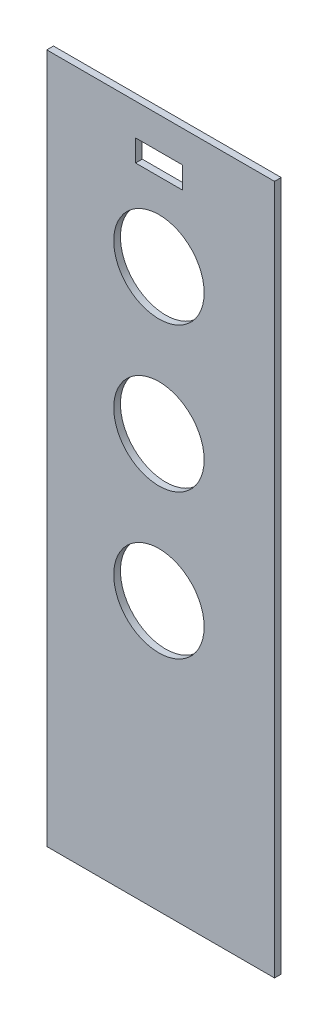
SolidWorks part; units mm, degrees
ref_plane "Front Plane" through (0, 0, 0) normal (0, 0, 1) x (1, 0, 0)
ref_plane "Top Plane" through (0, 0, 0) normal (0, 1, 0) x (1, 0, 0)
ref_plane "Right Plane" through (0, 0, 0) normal (1, 0, 0) x (0, 0, -1)
sketch "Sketch1" plane through (0, 0, 0) normal (0, 0, 1) x (1, 0, 0)
  line L0 (-17, 51.5) -> (17, -51.5) construction
  line L1 (-17, 51.5) -> (17, 51.5)
  line L2 (-17, 51.5) -> (-17, -51.5)
  line L3 (-17, -51.5) -> (17, -51.5)
  line L4 (17, 51.5) -> (17, -51.5)
  line L5 (17, 51.5) -> (-17, -51.5) construction
  point P4 (0, 0)
  dimension "D1" = 103
  dimension "D2" = 34
extrude "Boss-Extrude1" add sketch "Sketch1" along normal mid plane 1
sketch "Sketch3" plane through (0, 0, 0.5) normal (0, 0, 1) x (1, 0, 0)
  line L0 (0, 0) -> (0, 31.8277) construction
  line L1 (-3.75, 43.5) -> (3.25, 43.5)
  line L2 (-3.75, 43.5) -> (-3.75, 46.75)
  line L3 (-3.75, 46.75) -> (3.25, 46.75)
  line L4 (3.25, 43.5) -> (3.25, 46.75)
  line L5 (0, 31.8277) -> (-0.2558, 31.8277) construction
  line L6 (-0.2558, 31.8277) -> (-0.2558, -11.3524) construction
  circle A0 centre (-0.2558, 31.8277) radius 6.75
  circle A1 centre (-0.2558, 10.2376) radius 6.75
  circle A2 centre (-0.2558, -11.3524) radius 6.75
  dimension "D5" = 13.5
  dimension "D6" = 31.8277
  dimension "D7" = 0.2558
  dimension "D1" = 3.25
  dimension "D2" = 7
  dimension "D3" = 43.5
  dimension "D4" = 3.25
  dimension "D9" = 43.1801
  dimension "D8" = 3
extrude "Cut-Extrude1" cut sketch "Sketch3" against normal through all
